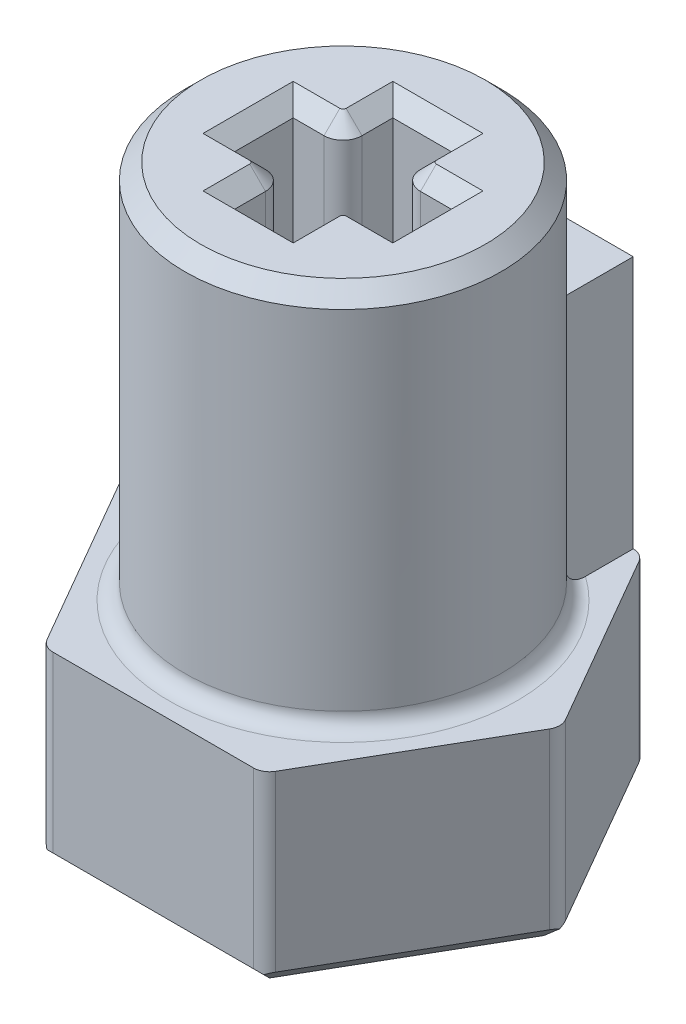
SolidWorks part; units mm, degrees
ref_plane "正面" through (0, 0, 0) normal (0, 0, 1) x (1, 0, 0)
ref_plane "平面" through (0, 0, 0) normal (0, 1, 0) x (1, 0, 0)
ref_plane "右側面" through (0, 0, 0) normal (1, 0, 0) x (0, 0, -1)
sketch "ｽｹｯﾁ1" plane through (0, 0, 0) normal (0, 1, 0) x (1, 0, 0)
  line L1 (-2.5, 0.925) -> (2.5, 0.925)
  line L2 (-2.5, 0.925) -> (-2.5, -0.925)
  line L3 (-2.5, -0.925) -> (2.5, -0.925)
  line L4 (2.5, 0.925) -> (2.5, -0.925)
  line L5 (-2.5, 0.925) -> (2.5, -0.925) construction
  line L6 (-2.5, -0.925) -> (2.5, 0.925) construction
  line L7 (-0.925, 2.5) -> (0.925, 2.5)
  line L8 (-0.925, 2.5) -> (-0.925, -2.5)
  line L9 (-0.925, -2.5) -> (0.925, -2.5)
  line L10 (0.925, 2.5) -> (0.925, -2.5)
  line L11 (-0.925, 2.5) -> (0.925, -2.5) construction
  line L12 (-0.925, -2.5) -> (0.925, 2.5) construction
  circle A0 centre (0, 0) radius 5
  dimension "D1" = 10
  dimension "D2" = 1.85
  dimension "D3" = 5
extrude "ﾎﾞｽ - 押し出し4" add sketch "ｽｹｯﾁ1" along normal blind 12 contours A0 | L8 L7 L10 L9 | L2 L1 L4 L3
fillet "ﾌｨﾚｯﾄ1" radius 0.6 1 edges at (0.925, 6, -0.925)
fillet "ﾌｨﾚｯﾄ2" radius 0.6 3 edges at (-0.925, 6, 0.925) (-0.925, 6, -0.925) (0.925, 6, 0.925)
sketch "ｽｹｯﾁ2" plane through (0, 0, 0) normal (0, -1, 0) x (1, 0, 0)
  line L1 (6.9282, 0) -> (3.4641, 6)
  line L2 (3.4641, 6) -> (-3.4641, 6)
  line L3 (-3.4641, 6) -> (-6.9282, 0)
  line L4 (-6.9282, 0) -> (-3.4641, -6)
  line L5 (-3.4641, -6) -> (3.4641, -6)
  line L6 (3.4641, -6) -> (6.9282, 0)
  circle A0 centre (0, 0) radius 6 construction
extrude "ﾎﾞｽ - 押し出し5" add sketch "ｽｹｯﾁ2" along normal blind 6
sketch "ｽｹｯﾁ3" plane through (0, -6, 0) normal (0, -1, 0) x (1, 0, 0)
  circle A0 centre (0, 0) radius 2.55
  dimension "D1" = 5.1
extrude "ｶｯﾄ - 押し出し1" cut sketch "ｽｹｯﾁ3" against normal blind 6 contours A0
chamfer "面取り1" distance 0.5 angle 45 7 edges at (0, -6, -6) (-5.1962, -6, -3) (-5.1962, -6, 3) (0, -6, 6) (5.1962, -6, 3) (5.1962, -6, -3) (0, -6, -2.55)
chamfer "面取り4" distance 0.5 angle 45 17 edges at (0, 12, 2.5) (0.925, 12, 2.0125) (1.1007, 12, 1.1007) (2.0125, 12, 0.925) (2.5, 12, 0) (2.0125, 12, -0.925) (1.1007, 12, -1.1007) (0.925, 12, -2.0125) (0, 12, -2.5) (-0.925, 12, -2.0125) (-1.1007, 12, -1.1007) (-2.0125, 12, -0.925) (-2.5, 12, 0) (-2.0125, 12, 0.925) (-1.1007, 12, 1.1007) (-0.925, 12, 2.0125) (0, 12, 5)
fillet "ﾌｨﾚｯﾄ4" radius 0.5 1 edges at (-3.4641, -2.75, 6)
fillet "ﾌｨﾚｯﾄ5" radius 0.5 5 edges at (-6.9282, -2.75, 0) (-3.4641, -2.75, -6) (3.4641, -2.75, -6) (6.9282, -2.75, 0) (3.4641, -2.75, 6)
sketch "ｽｹｯﾁ4" plane through (0, 0, -2.5) normal (0, 0, 1) x (1, 0, 0)
  line L6 (-3.1538, 0) -> (3.1754, 0)
  line L7 (-3.1538, 0) -> (-3.1538, 8)
  line L8 (-3.1538, 8) -> (3.1754, 8)
  line L9 (3.1754, 0) -> (3.1754, 8)
  dimension "D1" = 8
extrude "ﾎﾞｽ - 押し出し6" add sketch "ｽｹｯﾁ4" against normal up to surface (3.5 mm away) up to face at (0, -2.75, -6)
sketch "ｽｹｯﾁ5" plane through (0, 0, -6) normal (0, 0, -1) x (-1, 0, 0)
  circle A0 centre (0, 5) radius 1.2
  dimension "D1" = 2.4
  dimension "D2" = 5
extrude "ｶｯﾄ - 押し出し2" cut sketch "ｽｹｯﾁ5" against normal up to surface (3.5 mm away) up to face at (0, 3.8333, -2.5)
fillet "ﾌｨﾚｯﾄ7" radius 0.5 1 edges at (-0.014, 0, 5)
